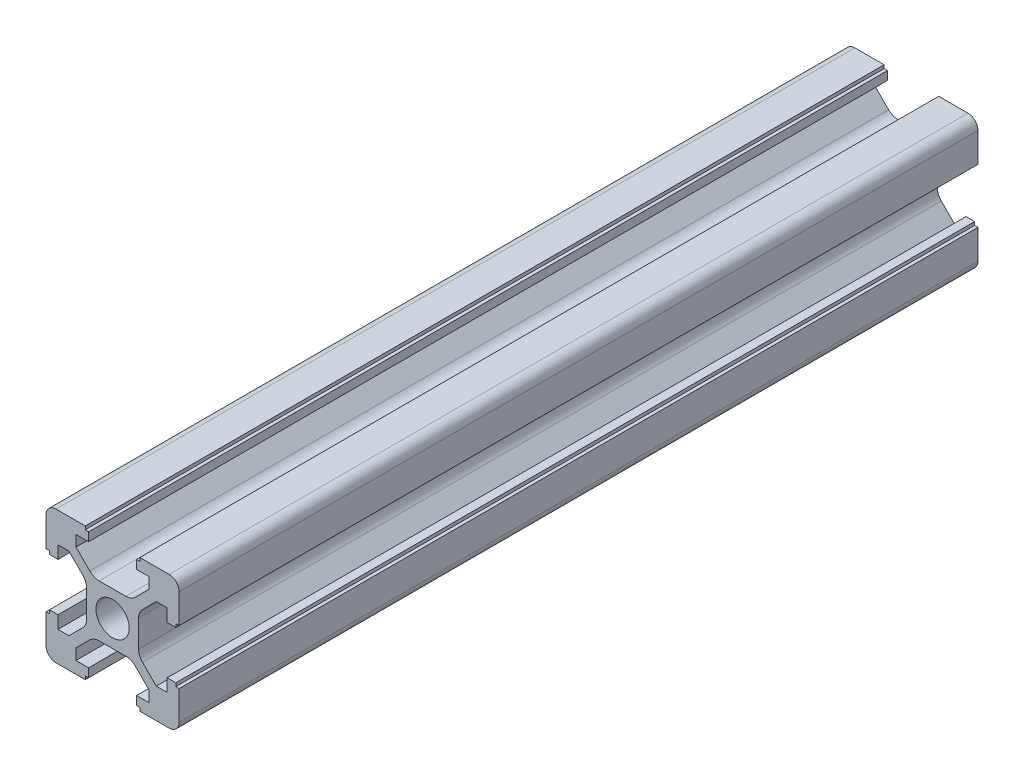
SolidWorks part; units mm, degrees
ref_plane "Front Plane" through (0, 0, 0) normal (0, 0, 1) x (1, 0, 0)
ref_plane "Top Plane" through (0, 0, 0) normal (0, 1, 0) x (1, 0, 0)
ref_plane "Right Plane" through (0, 0, 0) normal (1, 0, 0) x (0, 0, -1)
sketch "Sketch1" plane through (0, 0, 0) normal (0, 0, 1) x (1, 0, 0)
  line L0 (10, -4.1) -> (10, -8.5)
  line L1 (4.1, 10) -> (8.5, 10)
  line L2 (8.5, -10) -> (4.1, -10)
  line L3 (-8.5, -10) -> (-4.1, -10)
  line L4 (10, 8.5) -> (10, 4.1)
  line L7 (8.5, 10) -> (4.1, 10)
  line L8 (5.5, 6.5607) -> (3.4251, 4.4858)
  line L9 (8.5, 10) -> (4.1, 10)
  line L10 (3.9, 2.0109) -> (3.9, -2.0109)
  line L11 (2.0109, -3.9) -> (-2.0109, -3.9)
  line L12 (-3.9, -2.0109) -> (-3.9, 2.0109)
  line L13 (-2.0109, 3.9) -> (2.8393, 3.9)
  line L14 (2.5, 0) -> (22.2403, 0) construction
  line L15 (3.6, 9.5) -> (3.6, 8.2)
  line L16 (9.5, 3.6) -> (8.2, 3.6)
  line L17 (8.2, 3.6) -> (8.2, 5.5)
  line L18 (8.2, 5.5) -> (6.5607, 5.5)
  line L19 (10, -4.1) -> (10, -8.5)
  line L20 (4.1, 9.5) -> (3.6, 9.5)
  line L21 (4.1, 10) -> (4.1, 9.5)
  line L22 (8.5, 10) -> (4.1, 10)
  line L23 (10, 4.1) -> (9.5, 4.1)
  line L24 (9.5, 4.1) -> (9.5, 3.6)
  line L25 (5.5, 8.2) -> (5.5, 6.5607)
  line L26 (3.6, 8.2) -> (5.5, 8.2)
  line L27 (4.4858, 3.4251) -> (6.5607, 5.5)
  line L28 (10, -8.5) -> (10, -4.1)
  line L29 (6.5607, -5.5) -> (4.4858, -3.4251)
  line L30 (10, -8.5) -> (10, -4.1)
  line L31 (2.0109, -3.9) -> (-2.0109, -3.9)
  line L32 (3.9, 2.8393) -> (3.9, -2.0109)
  line L33 (9.5, -3.6) -> (8.2, -3.6)
  line L34 (3.6, -9.5) -> (3.6, -8.2)
  line L35 (3.6, -8.2) -> (5.5, -8.2)
  line L36 (5.5, -8.2) -> (5.5, -6.5607)
  line L37 (9.5, -4.1) -> (9.5, -3.6)
  line L38 (10, -4.1) -> (9.5, -4.1)
  line L39 (10, -8.5) -> (10, -4.1)
  line L40 (4.1, -10) -> (4.1, -9.5)
  line L41 (4.1, -9.5) -> (3.6, -9.5)
  line L42 (8.2, -5.5) -> (6.5607, -5.5)
  line L43 (8.2, -3.6) -> (8.2, -5.5)
  line L44 (3.4251, -4.4858) -> (5.5, -6.5607)
  line L45 (-4.1, -10) -> (-8.5, -10)
  line L46 (-10, -8.5) -> (-10, -4.1)
  line L47 (-8.5, -10) -> (-4.1, -10)
  line L48 (-5.5, -6.5607) -> (-3.4251, -4.4858)
  line L49 (-8.5, -10) -> (-4.1, -10)
  line L50 (-3.9, -2.0109) -> (-3.9, 2.0109)
  line L51 (2.0109, -3.9) -> (-2.0109, -3.9)
  line L52 (-3.6, -9.5) -> (-3.6, -8.2)
  line L53 (-9.5, -3.6) -> (-8.2, -3.6)
  line L54 (-8.2, -3.6) -> (-8.2, -5.5)
  line L55 (-8.2, -5.5) -> (-6.5607, -5.5)
  line L56 (-4.1, -9.5) -> (-3.6, -9.5)
  line L57 (-4.1, -10) -> (-4.1, -9.5)
  line L58 (-8.5, -10) -> (-4.1, -10)
  line L59 (-10, -4.1) -> (-9.5, -4.1)
  line L60 (-9.5, -4.1) -> (-9.5, -3.6)
  line L61 (-5.5, -8.2) -> (-5.5, -6.5607)
  line L62 (-3.6, -8.2) -> (-5.5, -8.2)
  line L63 (-4.4858, -3.4251) -> (-6.5607, -5.5)
  line L64 (-10, 4.1) -> (-10, 8.5)
  line L65 (-8.5, 10) -> (-4.1, 10)
  line L66 (-10, 8.5) -> (-10, 4.1)
  line L67 (-6.5607, 5.5) -> (-4.4858, 3.4251)
  line L68 (-10, 8.5) -> (-10, 4.1)
  line L69 (-2.0109, 3.9) -> (2.0109, 3.9)
  line L70 (-3.9, -2.0109) -> (-3.9, 2.0109)
  line L71 (-9.5, 3.6) -> (-8.2, 3.6)
  line L72 (-3.6, 9.5) -> (-3.6, 8.2)
  line L73 (-3.6, 8.2) -> (-5.5, 8.2)
  line L74 (-5.5, 8.2) -> (-5.5, 6.5607)
  line L75 (-9.5, 4.1) -> (-9.5, 3.6)
  line L76 (-10, 4.1) -> (-9.5, 4.1)
  line L77 (-10, 8.5) -> (-10, 4.1)
  line L78 (-4.1, 10) -> (-4.1, 9.5)
  line L79 (-4.1, 9.5) -> (-3.6, 9.5)
  line L80 (-8.2, 5.5) -> (-6.5607, 5.5)
  line L81 (-8.2, 3.6) -> (-8.2, 5.5)
  line L82 (-3.4251, 4.4858) -> (-5.5, 6.5607)
  line L83 (4.1, -10) -> (8.5, -10)
  arc A0 (2.0109, -3.9) -> (3.4251, -4.4858) centre (2.0109, -5.9) cw
  arc A1 (4.4858, -3.4251) -> (3.9, -2.0109) centre (5.9, -2.0109) cw
  arc A2 (3.9, 2.0109) -> (4.4858, 3.4251) centre (5.9, 2.0109) cw
  arc A3 (2.0109, 3.9) -> (3.4251, 4.4858) centre (2.0109, 5.9) ccw
  arc A4 (-2.0109, 3.9) -> (-3.4251, 4.4858) centre (-2.0109, 5.9) cw
  arc A5 (-4.4858, 3.4251) -> (-3.9, 2.0109) centre (-5.9, 2.0109) cw
  arc A6 (-3.4251, -4.4858) -> (-2.0109, -3.9) centre (-2.0109, -5.9) cw
  arc A7 (-3.9, -2.0109) -> (-4.4858, -3.4251) centre (-5.9, -2.0109) cw
  circle A8 centre (0, 0) radius 2.5
  arc A9 (-8.5, -10) -> (-10, -8.5) centre (-8.5, -8.5) cw
  arc A10 (-10, 8.5) -> (-8.5, 10) centre (-8.5, 8.5) cw
  arc A11 (8.5, 10) -> (10, 8.5) centre (8.5, 8.5) cw
  arc A12 (8.5, -10) -> (10, -8.5) centre (8.5, -8.5) ccw
  point P0 (0, 0)
  point P86 (0, 0)
  point P107 (10, -10)
  dimension "D3" = 2
  dimension "D5" = 5
  dimension "D2" = 1.5
  dimension "D8" = 1.5
  dimension "D4" = 6.1
  dimension "D6" = 20
  dimension "D7" = 6.1
  dimension "D9" = 20
  dimension "D11" = 0.5
  dimension "D12" = 0.5
extrude "Boss-Extrude2" add sketch "Sketch1" along normal blind 120
